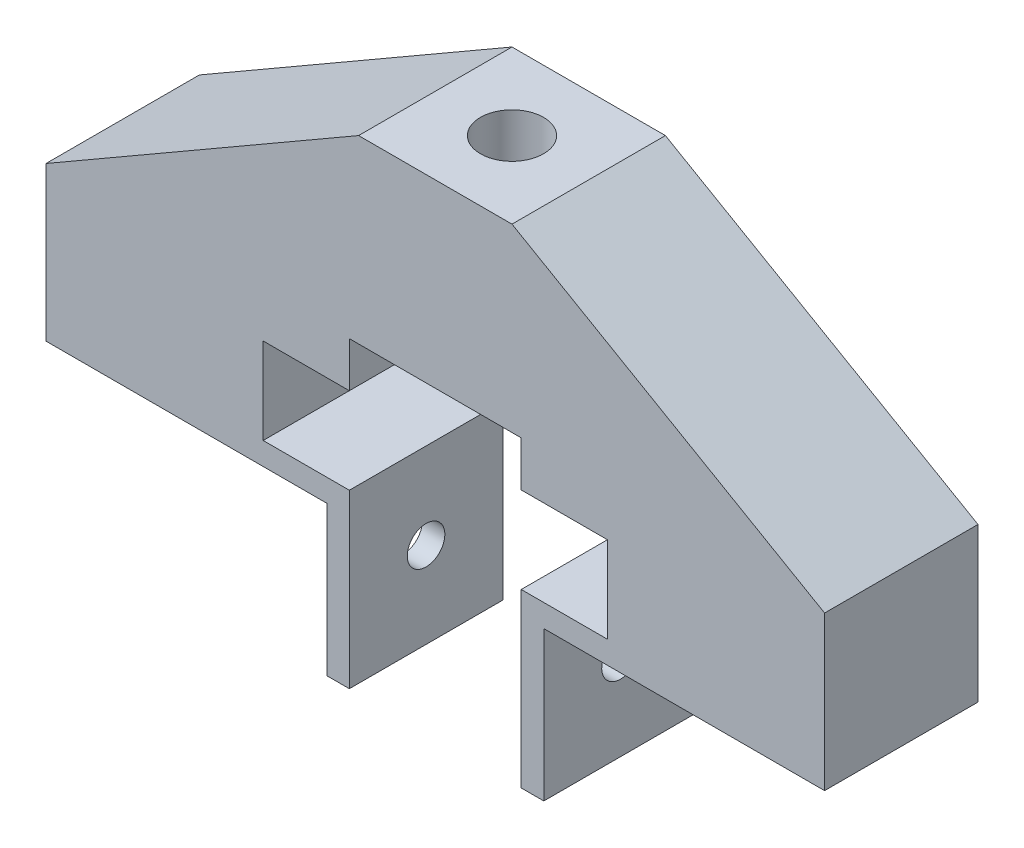
SolidWorks part; units mm, degrees
material "Polyester Resin"
ref_plane "Front Plane" through (0, 0, 0) normal (0, 0, 1) x (1, 0, 0)
ref_plane "Top Plane" through (0, 0, 0) normal (0, 1, 0) x (1, 0, 0)
ref_plane "Right Plane" through (0, 0, 0) normal (1, 0, 0) x (0, 0, -1)
sketch "Sketch1" plane through (0, 0, 0) normal (0, 0, 1) x (1, 0, 0)
  line L0 (-86.282, 0) -> (-24.05, 0)
  line L1 (-24.05, 0) -> (-24.05, -33.1)
  line L2 (-24.05, -33.1) -> (-19.05, -33.1)
  line L3 (-19.05, -33.1) -> (-19.05, 5)
  line L4 (-19.05, 5) -> (-38.15, 5)
  line L5 (-38.15, 5) -> (-38.15, 24.1)
  line L6 (-38.15, 24.1) -> (-19.05, 24.1)
  line L7 (38.15, 24.1) -> (38.15, 5)
  line L8 (38.15, 5) -> (19.05, 5)
  line L9 (19.05, 5) -> (19.05, -33.1)
  line L10 (19.05, -33.1) -> (24.05, -33.1)
  line L11 (24.05, -33.1) -> (24.05, 0)
  line L12 (24.05, 0) -> (86.282, 0)
  line L13 (86.282, 34.1) -> (17, 74.1)
  line L14 (17, 74.1) -> (-17, 74.1)
  line L15 (-17, 74.1) -> (-86.282, 34.1)
  line L16 (-19.05, 24.1) -> (-19.05, 34.1)
  line L17 (-19.05, 34.1) -> (19.05, 34.1)
  line L18 (19.05, 34.1) -> (19.05, 24.1)
  line L19 (19.05, 24.1) -> (38.15, 24.1)
  line L20 (86.282, 34.1) -> (-86.282, 34.1) construction
  line L21 (-86.282, 34.1) -> (-86.282, 0)
  line L22 (86.282, 34.1) -> (86.282, 0)
  point P18 (0, 74.1)
  point P22 (0, 34.1)
  dimension "D1" = 30
  dimension "D2" = 10
  dimension "D3" = 34
  dimension "D4" = 38.1
  dimension "D5" = 76.3
  dimension "D6" = 19.1
  dimension "D7" = 5
  dimension "D8" = 5
  dimension "D9" = 38.1
  dimension "D10" = 38.1
  dimension "D11" = 40
extrude "Boss-Extrude1" add sketch "Sketch1" along normal blind 34
sketch "Sketch2" plane through (0, 74.1, 0) normal (0, 1, 0) x (1, 0, 0)
  line L0 (-17, 0) -> (17, -34) construction
  line L1 (17, 0) -> (-17, -34) construction
  circle A0 centre (0, -17) radius 7
  dimension "D1" = 14
extrude "Cut-Extrude1" cut sketch "Sketch2" against normal blind 35
sketch "Sketch3" plane through (24.05, 0, 0) normal (1, 0, 0) x (0, 0, -1)
  line L0 (-17, -33.1) -> (-17, 0) construction
  line L1 (-34, -33.1) -> (0, -33.1) construction
  line L2 (-34, 0) -> (0, 0) construction
  circle A0 centre (-17, -14.05) radius 4.1656
  dimension "D1" = 8.3312
  dimension "D2" = 19.05
extrude "Cut-Extrude2" cut sketch "Sketch3" against normal through all
